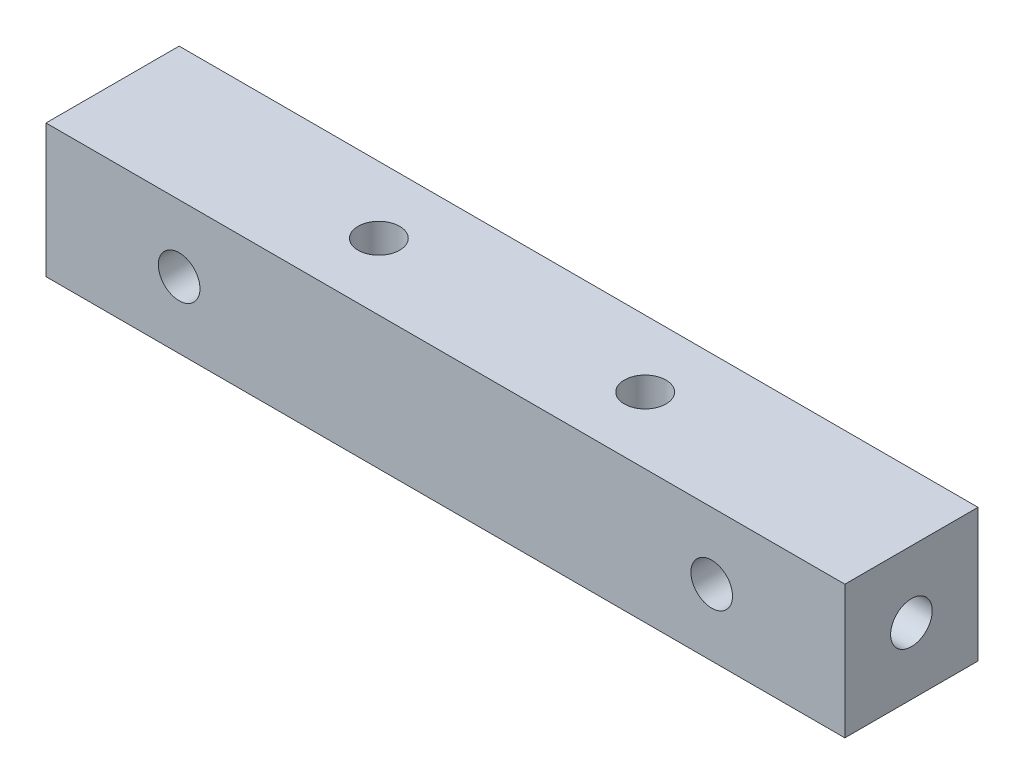
SolidWorks part; units mm, degrees
material "6061 合金"
ref_plane "前视基准面" through (0, 0, 0) normal (0, 0, 1) x (1, 0, 0)
ref_plane "上视基准面" through (0, 0, 0) normal (0, 1, 0) x (1, 0, 0)
ref_plane "右视基准面" through (0, 0, 0) normal (1, 0, 0) x (0, 0, -1)
sketch "草图1" plane through (0, 0, 0) normal (0, 0, 1) x (1, 0, 0)
  line L1 (24, -4) -> (-24, -4)
  line L2 (24, -4) -> (24, 4)
  line L3 (24, 4) -> (-24, 4)
  line L4 (-24, -4) -> (-24, 4)
  line L5 (24, -4) -> (-24, 4) construction
  line L6 (24, 4) -> (-24, -4) construction
  point P0 (0, 0)
  dimension "D1" = 48
  dimension "D2" = 8
extrude "凸台-拉伸1" add sketch "草图1" along normal blind 8
sketch "草图2" plane through (-24, 0, 0) normal (-1, 0, 0) x (0, 0, 1)
  line L0 (0, 4) -> (8, -4) construction
  line L1 (8, 4) -> (8, -4) construction
  line L2 (8, -4) -> (0, -4) construction
  line L3 (8, 4) -> (0, -4) construction
  point P11 (4, 0)
hole_wizard "M3 螺纹孔的螺纹孔钻头1" positions "3D草图1" profile "草图3" hole size "M3" standard "DIN" end condition through all
sketch3d "3D草图1"
  point P0 (-24, 0, 4)
sketch "草图3" plane through (-24, 0, 4) normal (0, 1, 0) x (0, 0, 1)
  line L0 (0, 0) -> (0, 48)
  line L1 (0, 48) -> (1.25, 48)
  line L2 (1.25, 48) -> (1.25, 0)
  line L5 (1.25, 0) -> (0, 0)
  line L11 (0, -6.35) -> (0, 107.95) construction
  dimension "通孔孔直径" = 2.5
  dimension "通孔孔深度" = 48
sketch "草图4" plane through (0, 0, 8) normal (0, 0, 1) x (1, 0, 0)
  line L0 (-24, 4) -> (-24, -4) construction
  line L1 (24, -4) -> (24, 4) construction
  point P0 (-16, 0)
  point P1 (16, 0)
  dimension "D1" = 8
  dimension "D2" = 8
hole_wizard "M3 螺纹孔的螺纹孔钻头2" positions "3D草图2" profile "草图5" hole size "M3" standard "DIN" end condition through all
sketch3d "3D草图2"
  point P0 (-16, 0, 8)
sketch "草图5" plane through (-16, 0, 8) normal (1, 0, 0) x (0, -1, 0)
  line L0 (0, 0) -> (0, 8)
  line L1 (0, 8) -> (1.25, 8)
  line L2 (1.25, 8) -> (1.25, 0)
  line L5 (1.25, 0) -> (0, 0)
  line L11 (0, -6.35) -> (0, 107.95) construction
  dimension "通孔孔直径" = 2.5
  dimension "通孔孔深度" = 8
hole_wizard "M3 螺纹孔的螺纹孔钻头3" positions "3D草图3" profile "草图6" hole size "M3" standard "DIN" end condition through all
sketch3d "3D草图3"
  point P0 (16, 0, 8)
sketch "草图6" plane through (16, 0, 8) normal (1, 0, 0) x (0, -1, 0)
  line L0 (0, 0) -> (0, 8)
  line L1 (0, 8) -> (1.25, 8)
  line L2 (1.25, 8) -> (1.25, 0)
  line L5 (1.25, 0) -> (0, 0)
  line L11 (0, -6.35) -> (0, 107.95) construction
  dimension "通孔孔直径" = 2.5
  dimension "通孔孔深度" = 8
sketch "草图7" plane through (0, 4, 0) normal (0, 1, 0) x (1, 0, 0)
  line L0 (-24, -8) -> (-24, 0) construction
  line L1 (24, -8) -> (24, 0) construction
  point P0 (-8, -4)
  point P1 (8, -4)
  dimension "D1" = 16
  dimension "D2" = 16
hole_wizard "M3 螺纹孔的螺纹孔钻头4" positions "3D草图4" profile "草图8" hole size "M3" standard "DIN" end condition through all
sketch3d "3D草图4"
  point P0 (-8, 4, 4)
sketch "草图8" plane through (-8, 4, 4) normal (1, 0, 0) x (0, 0, 1)
  line L0 (0, 0) -> (0, 8)
  line L1 (0, 8) -> (1.25, 8)
  line L2 (1.25, 8) -> (1.25, 0)
  line L5 (1.25, 0) -> (0, 0)
  line L11 (0, -6.35) -> (0, 107.95) construction
  dimension "通孔孔直径" = 2.5
  dimension "通孔孔深度" = 8
hole_wizard "M3 螺纹孔的螺纹孔钻头5" positions "3D草图5" profile "草图9" hole size "M3" standard "DIN" end condition through all
sketch3d "3D草图5"
  point P0 (8, 4, 4)
sketch "草图9" plane through (8, 4, 4) normal (1, 0, 0) x (0, 0, 1)
  line L0 (0, 0) -> (0, 8)
  line L1 (0, 8) -> (1.25, 8)
  line L2 (1.25, 8) -> (1.25, 0)
  line L5 (1.25, 0) -> (0, 0)
  line L11 (0, -6.35) -> (0, 107.95) construction
  dimension "通孔孔直径" = 2.5
  dimension "通孔孔深度" = 8
